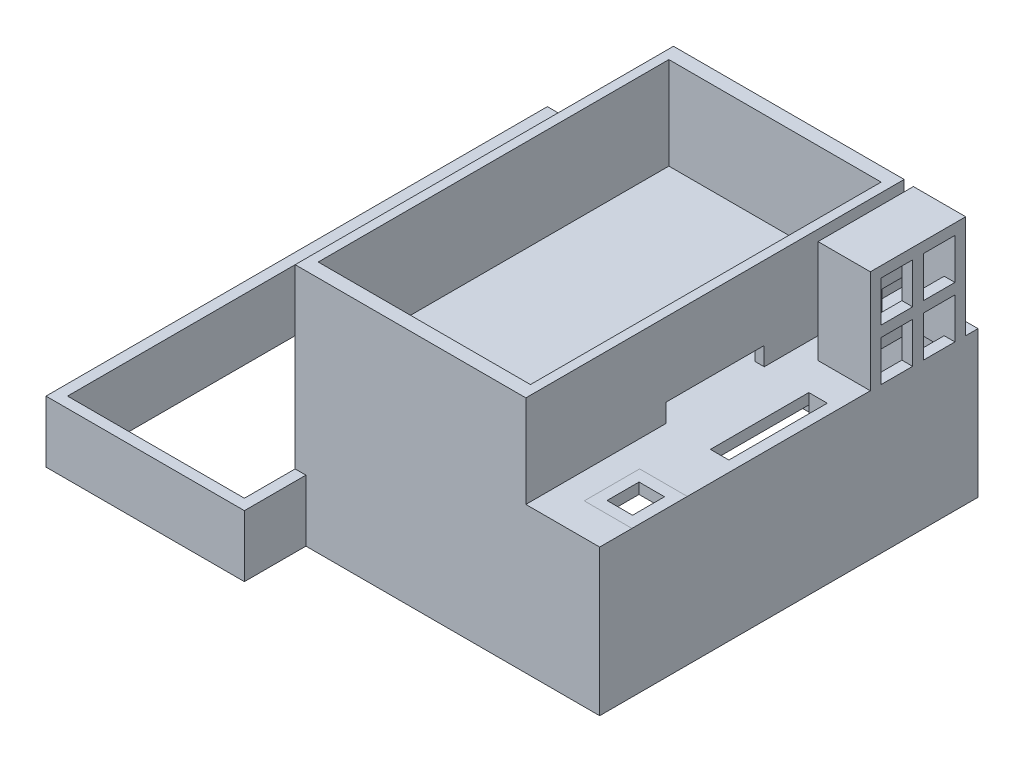
SolidWorks part; units mm, degrees
ref_plane "Front Plane" through (0, 0, 0) normal (0, 0, 1) x (1, 0, 0)
ref_plane "Top Plane" through (0, 0, 0) normal (0, 1, 0) x (1, 0, 0)
ref_plane "Right Plane" through (0, 0, 0) normal (1, 0, 0) x (0, 0, -1)
sketch "Sketch1" plane through (0, 0, 0) normal (0, 1, 0) x (1, 0, 0)
  line L1 (-138.162, -76.1412) -> (-88.662, -76.1412)
  line L2 (-138.162, -76.1412) -> (-138.162, -14.6412)
  line L3 (-138.162, -14.6412) -> (-88.662, -14.6412)
  line L4 (-88.662, -76.1412) -> (-88.662, -14.6412)
  dimension "D1" = 49.5
  dimension "D2" = 61.5
extrude "Boss-Extrude1" add sketch "Sketch1" along normal blind 23.75
sketch "Sketch2" plane through (0, 0, 0) normal (0, -1, 0) x (-1, 0, 0)
  line L0 (138.162, -76.1412) -> (88.662, -76.1412) construction
  line L1 (90.412, -74.3912) -> (136.412, -74.3912)
  line L2 (90.412, -74.3912) -> (90.412, -16.3912)
  line L3 (90.412, -16.3912) -> (136.412, -16.3912)
  line L4 (136.412, -74.3912) -> (136.412, -16.3912)
  line L5 (88.662, -76.1412) -> (88.662, -14.6412) construction
  line L6 (88.662, -14.6412) -> (138.162, -14.6412) construction
  line L7 (138.162, -14.6412) -> (138.162, -76.1412) construction
  dimension "D1" = 1.75
  dimension "D2" = 1.75
  dimension "D3" = 1.75
  dimension "D4" = 1.75
extrude "Cut-Extrude1" cut sketch "Sketch2" against normal blind 22
sketch "Sketch3" plane through (0, 22, 0) normal (0, -1, 0) x (-1, 0, 0)
  line L0 (136.412, -16.3912) -> (90.412, -16.3912) construction
  line L1 (90.412, -74.3912) -> (93.412, -74.3912)
  line L2 (90.412, -74.3912) -> (90.412, -16.3912)
  line L3 (90.412, -16.3912) -> (93.412, -16.3912)
  line L4 (93.412, -74.3912) -> (93.412, -16.3912)
  line L6 (90.412, -58.3912) -> (93.412, -58.3912)
  line L7 (90.412, -58.3912) -> (90.412, -53.3912)
  line L8 (90.412, -53.3912) -> (93.412, -53.3912)
  line L9 (93.412, -58.3912) -> (93.412, -53.3912)
  line L10 (90.412, -37.3912) -> (93.412, -37.3912)
  line L11 (90.412, -37.3912) -> (90.412, -32.3912)
  line L12 (90.412, -32.3912) -> (93.412, -32.3912)
  line L13 (93.412, -37.3912) -> (93.412, -32.3912)
  line M9 (90.412, -16.3912) -> (90.412, -74.3912)
  line M10 (90.412, -74.3912) -> (136.412, -74.3912)
  line M12 (136.412, -16.3912) -> (90.412, -16.3912)
  dimension "D1" = 3
  dimension "D2" = 5
  dimension "D3" = 5
  dimension "D4" = 16
  dimension "D5" = 16
extrude "Cut-Extrude2" cut sketch "Sketch3" against normal blind 1.75 contours L6 L2 L4 M10 | L12 L4 M9 M12 | L10 L2 L8 L4
sketch "Sketch7" plane through (0, 22, 0) normal (0, -1, 0) x (-1, 0, 0)
  line L1 (90.412, -58.3912) -> (93.412, -58.3912)
  line L2 (90.412, -58.3912) -> (90.412, -53.3912)
  line L3 (90.412, -53.3912) -> (93.412, -53.3912)
  line L4 (93.412, -58.3912) -> (93.412, -53.3912)
  line L5 (90.412, -37.3912) -> (93.412, -37.3912)
  line L6 (90.412, -37.3912) -> (90.412, -32.3912)
  line L7 (90.412, -32.3912) -> (93.412, -32.3912)
  line L8 (93.412, -37.3912) -> (93.412, -32.3912)
extrude "Boss-Extrude2" add sketch "Sketch7" along normal blind 4 contours L2 L1 L4 L3 | L6 L5 L8 L7
sketch "Sketch9" plane through (-93.412, 0, 0) normal (-1, 0, 0) x (0, 0, 1)
  line L0 (58.3912, 18) -> (58.3912, 22) construction
  line L1 (58.3912, 20.407) -> (53.3912, 20.407)
  line L2 (58.3912, 20.407) -> (58.3912, 22)
  line L3 (58.3912, 22) -> (53.3912, 22)
  line L4 (53.3912, 20.407) -> (53.3912, 22)
sketch "Sketch11" plane through (0, 23.75, 0) normal (0, 1, 0) x (1, 0, 0)
  line L0 (-138.162, -76.1412) -> (-88.662, -76.1412) construction
  line L1 (-138.162, -14.6412) -> (-100.662, -14.6412)
  line L2 (-138.162, -14.6412) -> (-138.162, -76.1412)
  line L3 (-138.162, -76.1412) -> (-100.662, -76.1412)
  line L4 (-100.662, -14.6412) -> (-100.662, -76.1412)
  dimension "D1" = 37.5
extrude "Boss-Extrude3" add sketch "Sketch11" along normal blind 15
sketch "Sketch12" plane through (0, 38.75, 0) normal (0, 1, 0) x (1, 0, 0)
  line L0 (-138.162, -14.6412) -> (-138.162, -76.1412) construction
  line L1 (-136.662, -16.8912) -> (-102.162, -16.8912)
  line L2 (-136.662, -16.8912) -> (-136.662, -73.8912)
  line L3 (-136.662, -73.8912) -> (-102.162, -73.8912)
  line L4 (-102.162, -16.8912) -> (-102.162, -73.8912)
  line L5 (-100.662, -76.1412) -> (-100.662, -14.6412) construction
  line L6 (-100.662, -14.6412) -> (-138.162, -14.6412) construction
  line L7 (-138.162, -76.1412) -> (-100.662, -76.1412) construction
  dimension "D1" = 1.5
  dimension "D2" = 1.5
  dimension "D3" = 2.25
  dimension "D4" = 2.25
extrude "Cut-Extrude3" cut sketch "Sketch12" against normal blind 15
sketch "Sketch14" plane through (0, 23.75, 0) normal (0, 1, 0) x (1, 0, 0)
  line L0 (-90.412, -58.3912) -> (-93.412, -58.3912) construction
  line L1 (-96.417, -70.8912) -> (-88.667, -70.8912)
  line L2 (-96.417, -70.8912) -> (-96.417, -61.8912)
  line L3 (-96.417, -61.8912) -> (-88.667, -61.8912)
  line L4 (-88.667, -70.8912) -> (-88.667, -61.8912)
  point P6 (-91.912, -58.3912)
  dimension "D1" = 9
  dimension "D2" = 7.75
  dimension "D3" = 3.5
  dimension "D4" = 3.245
extrude "Boss-Extrude4" add sketch "Sketch14" along normal blind 0.0001
sketch "Sketch15" plane through (0, 23.7501, 0) normal (0, 1, 0) x (1, 0, 0)
  line L0 (-96.417, -61.8912) -> (-96.417, -70.8912) construction
  line L1 (-94.617, -68.9912) -> (-90.467, -68.9912)
  line L2 (-94.617, -68.9912) -> (-94.617, -63.7912)
  line L3 (-94.617, -63.7912) -> (-90.467, -63.7912)
  line L4 (-90.467, -68.9912) -> (-90.467, -63.7912)
  line L5 (-88.667, -61.8912) -> (-96.417, -61.8912) construction
  line L6 (-88.667, -70.8912) -> (-88.667, -61.8912) construction
  line L7 (-96.417, -70.8912) -> (-88.667, -70.8912) construction
  dimension "D1" = 1.8
  dimension "D2" = 1.9
  dimension "D3" = 1.8
  dimension "D4" = 1.9
extrude "Cut-Extrude4" cut sketch "Sketch15" against normal blind 4.75
sketch "Sketch16" plane through (0, 23.75, 0) normal (0, 1, 0) x (1, 0, 0)
  line L0 (-93.412, -16.3912) -> (-90.412, -16.3912) construction
  line L1 (-97.162, -32.1412) -> (-88.662, -32.1412)
  line L2 (-97.162, -32.1412) -> (-97.162, -16.6412)
  line L3 (-97.162, -16.6412) -> (-88.662, -16.6412)
  line L4 (-88.662, -32.1412) -> (-88.662, -16.6412)
  line L5 (-93.412, -32.3912) -> (-93.412, -16.3912) construction
  point P6 (-91.912, -16.3912)
  point P9 (-93.412, -24.3912)
  dimension "D1" = 15.5
  dimension "D2" = 8.5
  dimension "D3" = 3.25
  dimension "D4" = 7.75
extrude "Boss-Extrude5" add sketch "Sketch16" along normal blind 16.75
sketch "Sketch17" plane through (-88.662, 0, 0) normal (1, 0, 0) x (0, 0, -1)
  line L0 (-32.1412, 40.5) -> (-16.6412, 40.5) construction
  line L1 (-30.3912, 38.75) -> (-25.2662, 38.75)
  line L2 (-30.3912, 38.75) -> (-30.3912, 23.75)
  line L3 (-30.3912, 23.75) -> (-25.2662, 23.75)
  line L4 (-25.2662, 38.75) -> (-25.2662, 23.75)
  line L5 (-23.5162, 38.75) -> (-18.3912, 38.75)
  line L6 (-23.5162, 38.75) -> (-23.5162, 23.75)
  line L7 (-23.5162, 23.75) -> (-18.3912, 23.75)
  line L8 (-18.3912, 38.75) -> (-18.3912, 23.75)
  line L9 (-32.1412, 40.5) -> (-32.1412, 23.75) construction
  line L10 (-16.6412, 40.5) -> (-16.6412, 23.75) construction
  line L11 (-16.6412, 23.75) -> (-14.6412, 23.75) construction
  line L12 (-76.1412, 23.75) -> (-32.1412, 23.75) construction
  line L14 (-32.1412, 32.125) -> (-16.6412, 32.125)
  line L15 (-32.1412, 32.125) -> (-32.1412, 30.375)
  line L16 (-32.1412, 30.375) -> (-16.6412, 30.375)
  line L17 (-16.6412, 32.125) -> (-16.6412, 30.375)
  dimension "D1" = 1.75
  dimension "D2" = 1.75
  dimension "D3" = 1.75
  dimension "D4" = 1.75
  dimension "D5" = 0
  dimension "D6" = 0
  dimension "D7" = 5.125
  dimension "D8" = 5.125
  dimension "D9" = 1.75
  dimension "D10" = 6.625
extrude "Cut-Extrude5" cut sketch "Sketch17" against normal blind 8.5 contours L2 L14 L4 L1 | L16 L2 L3 L4 | L6 L14 L8 L5 | L16 L6 L7 L8
sketch "Sketch18" plane through (0, 23.75, 0) normal (0, 1, 0) x (1, 0, 0)
  line L0 (-93.412, -18.3912) -> (-90.412, -18.3912) construction
  line L1 (-95.412, -30.3912) -> (-90.412, -30.3912)
  line L2 (-95.412, -30.3912) -> (-95.412, -18.3912)
  line L3 (-95.412, -18.3912) -> (-90.412, -18.3912)
  line L4 (-90.412, -30.3912) -> (-90.412, -18.3912)
  line L5 (-88.662, -30.3912) -> (-88.662, -25.2662) construction
  line L6 (-93.412, -30.3912) -> (-90.412, -30.3912) construction
  dimension "D1" = 0
  dimension "D2" = 1.75
  dimension "D3" = 1.75
  dimension "D4" = 0
extrude "Cut-Extrude6" cut sketch "Sketch18" against normal blind 1.75 and the other way blind 15
sketch "Sketch20" plane through (-100.662, 0, 0) normal (1, 0, 0) x (0, 0, -1)
  line L0 (-76.1412, 23.75) -> (-14.6412, 23.75) construction
  line L1 (-53.3912, 26.75) -> (-37.3912, 26.75)
  line L2 (-53.3912, 26.75) -> (-53.3912, 23.75)
  line L3 (-53.3912, 23.75) -> (-37.3912, 23.75)
  line L4 (-37.3912, 26.75) -> (-37.3912, 23.75)
  dimension "D1" = 3
  dimension "D2" = 0
  dimension "D3" = 0
extrude "Cut-Extrude7" cut sketch "Sketch20" against normal blind 1.75
sketch "Sketch21" plane through (0, 0, 0) normal (0, -1, 0) x (-1, 0, 0)
  line L0 (138.162, -14.6412) -> (138.162, -76.1412) construction
  line L1 (136.412, -86.1412) -> (168.662, -86.1412)
  line L2 (136.412, -86.1412) -> (136.412, -4.6412)
  line L3 (136.412, -4.6412) -> (168.662, -4.6412)
  line L4 (168.662, -86.1412) -> (168.662, -4.6412)
  line L5 (138.162, -76.1412) -> (88.662, -76.1412) construction
  line L6 (88.662, -14.6412) -> (138.162, -14.6412) construction
  dimension "D1" = 30.5
  dimension "D2" = 1.75
  dimension "D3" = 10
  dimension "D4" = 10
extrude "Boss-Extrude7" add sketch "Sketch21" against normal blind 10
sketch "Sketch23" plane through (0, 10, 0) normal (0, 1, 0) x (1, 0, 0)
  line L0 (-136.412, -86.1412) -> (-168.662, -86.1412) construction
  line L1 (-138.162, -84.3912) -> (-166.912, -84.3912)
  line L2 (-138.162, -84.3912) -> (-138.162, -6.3912)
  line L3 (-138.162, -6.3912) -> (-166.912, -6.3912)
  line L4 (-166.912, -84.3912) -> (-166.912, -6.3912)
  line L5 (-168.662, -86.1412) -> (-168.662, -4.6412) construction
  line L6 (-168.662, -4.6412) -> (-136.412, -4.6412) construction
  line L7 (-138.162, -14.6412) -> (-138.162, -76.1412) construction
  dimension "D1" = 1.75
  dimension "D2" = 1.75
  dimension "D3" = 1.75
  dimension "D4" = 0
extrude "Cut-Extrude8" cut sketch "Sketch23" against normal blind 10
sketch "Sketch24" plane through (0, 23.75, 0) normal (0, -1, 0) x (-1, 0, 0)
  line L1 (93.383, -63.5335) -> (90.412, -63.5335)
  line L2 (93.383, -63.5335) -> (93.383, -58.3912)
  line L3 (93.383, -58.3912) -> (90.412, -58.3912)
  line L4 (90.412, -63.5335) -> (90.412, -58.3912)
sketch "Sketch25" plane through (0, 22, 0) normal (0, -1, 0) x (-1, 0, 0)
  line L0 (90.412, -63.5335) -> (90.412, -58.3912) construction
  line L1 (93.412, -63.7912) -> (90.412, -63.7912)
  line L2 (93.412, -63.7912) -> (93.412, -58.3912)
  line L3 (93.412, -58.3912) -> (90.412, -58.3912)
  line L4 (90.412, -63.7912) -> (90.412, -58.3912)
  line L5 (93.383, -58.3912) -> (90.412, -58.3912) construction
  line L6 (93.412, -74.3912) -> (136.412, -74.3912) construction
  line L7 (93.412, -68.9912) -> (90.412, -68.9912)
  line L8 (93.412, -68.9912) -> (93.412, -74.3912)
  line L9 (93.412, -74.3912) -> (90.412, -74.3912)
  line L10 (90.412, -68.9912) -> (90.412, -74.3912)
  line L11 (90.412, -70.8912) -> (90.412, -61.8912) construction
  dimension "D1" = 0
  dimension "D2" = 0
  dimension "D3" = 0
  dimension "D4" = 0
extrude "Boss-Extrude8" add sketch "Sketch25" against normal blind 1.75
sketch "Sketch26" plane through (0, 23.75, 0) normal (0, 1, 0) x (1, 0, 0)
  line L1 (-93.412, -32.3912) -> (-90.412, -32.3912)
  line L2 (-93.412, -32.3912) -> (-93.412, -30.3912)
  line L3 (-93.412, -30.3912) -> (-90.412, -30.3912)
  line L4 (-90.412, -32.3912) -> (-90.412, -30.3912)
sketch "Sketch28" plane through (0, 23.75, 0) normal (0, 1, 0) x (1, 0, 0)
  line L0 (-90.412, -23.5162) -> (-90.412, -18.3912) construction
  line L1 (-93.412, -16.3912) -> (-90.412, -16.3912)
  line L2 (-93.412, -16.3912) -> (-93.412, -18.3912)
  line L3 (-93.412, -18.3912) -> (-90.412, -18.3912)
  line L4 (-90.412, -16.3912) -> (-90.412, -18.3912)
  line L6 (-90.412, -32.3912) -> (-93.412, -32.3912)
  line L7 (-90.412, -32.3912) -> (-90.412, -30.3912)
  line L8 (-90.412, -30.3912) -> (-93.412, -30.3912)
  line L9 (-93.412, -32.3912) -> (-93.412, -30.3912)
extrude "Boss-Extrude9" add sketch "Sketch28" against normal blind 1.75
